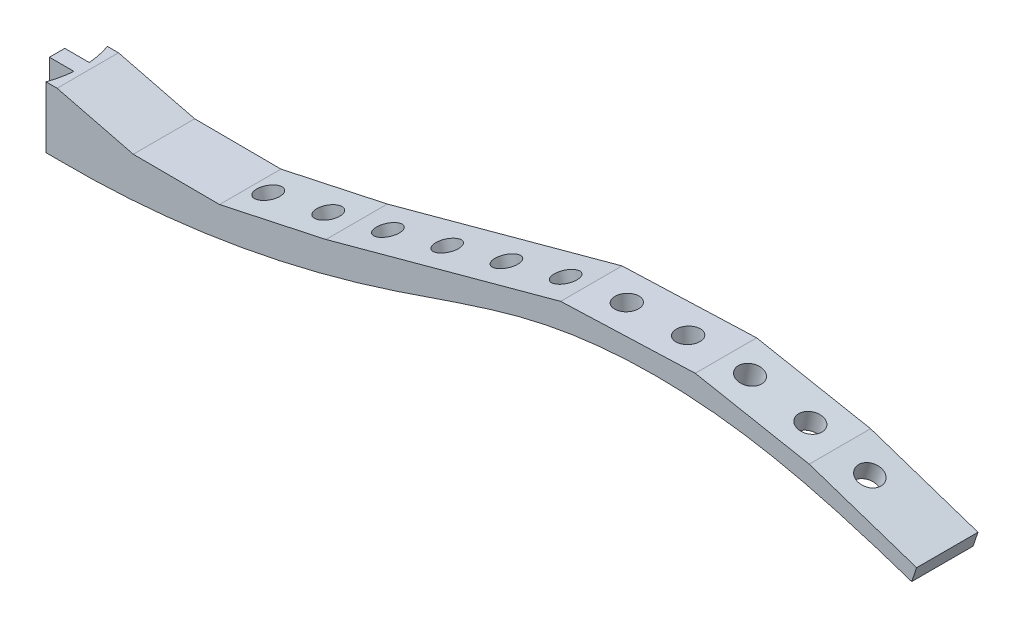
SolidWorks part; units mm, degrees
ref_plane "Front Plane" through (0, 0, 0) normal (0, 0, 1) x (1, 0, 0)
ref_plane "Top Plane" through (0, 0, 0) normal (0, 1, 0) x (1, 0, 0)
ref_plane "Right Plane" through (0, 0, 0) normal (1, 0, 0) x (0, 0, -1)
sketch "Sketch1" plane through (0, 0, 0) normal (0, 0, 1) x (1, 0, 0)
  line L0 (0, 0) -> (0, 12.7)
  line L1 (177.8, 15.7071) -> (176.7812, 12.7)
  line L2 (0, 12.7) -> (15.7663, 8.7557)
  line L3 (15.7663, 8.7557) -> (33.6079, 8.6702)
  line L4 (33.6079, 8.6702) -> (55.6141, 13.4119)
  line L5 (55.6141, 13.4119) -> (104.1724, 26.6053)
  line L6 (104.1724, 26.6053) -> (132.0034, 27.6381)
  line L7 (132.0034, 27.6381) -> (155.5781, 23.1472)
  line L8 (155.5781, 23.1472) -> (177.8, 15.7071)
  spline S1 degree 3 poles (0, 0) (23.0853, -0.2953) (56.9453, 5.5804) (102.5759, 23.5711) (140.7861, 23.9943) (166.1987, 16.2854) (176.7812, 12.7) knots 0 0 0 0 0.381953 0.565829 0.810764 1 1 1 1
  dimension "D1" = 12.7
  dimension "D2" = 3.175
  dimension "D3" = 177.8
  dimension "D4" = 12.7
extrude "Boss-Extrude1" add sketch "Sketch1" along normal mid plane 12.7
sketch "Sketch2" plane through (0, 0, 0) normal (0, 1, 0) x (1, 0, 0)
  line L0 (0, 6.35) -> (-2.2932, 6.35)
  line L1 (0, -6.35) -> (-2.2932, -6.35)
  line L2 (-1.27, 1.5875) -> (-6.35, 1.5875)
  line L3 (-6.35, 1.5875) -> (-6.35, -1.5875)
  line L4 (-6.35, -1.5875) -> (-1.27, -1.5875)
  line L5 (0, 6.35) -> (0, -6.35)
  line L7 (15.7663, 6.35) -> (0, 6.35) construction
  line L8 (15.7663, -6.35) -> (0, -6.35) construction
  line L9 (0, -6.35) -> (0, 6.35) construction
  arc A0 (-2.2932, 6.35) -> (-1.27, 1.5875) centre (-20.2537, 0) cw
  arc A1 (-1.27, -1.5875) -> (-2.2932, -6.35) centre (-20.2537, 0) cw
  point P7 (0, 0)
  point P12 (-6.35, 0)
  point P17 (0, 7.389)
  point P18 (0, 0)
  point P21 (2.6319, 6.35)
  dimension "D1" = 19.05
  dimension "D2" = 1.27
  dimension "D3" = 3.175
  dimension "D4" = 5.08
extrude "Boss-Extrude2" add sketch "Sketch2" along normal up to vertex (12.7 mm away) up to point (0, 12.7, 6.35)
sketch "Sketch4" plane through (-0.2942, 1.3653, 0) normal (-0.2106, 0.9776, 0) x (0.9776, 0.2106, 0)
  line L0 (34.6802, 0) -> (57.1914, 0) construction
  line L1 (34.6802, -6.35) -> (34.6802, 6.35) construction
  line L2 (57.1914, -6.35) -> (57.1914, 6.35) construction
  line L3 (38.4902, 0) -> (51.1902, 0) construction
  circle A0 centre (38.4902, 0) radius 2.4384
  circle A2 centre (51.1902, 0) radius 2.4384
  dimension "D1" = 4.8768
  dimension "D2" = 2
  dimension "D3" = 12.7
  dimension "D4" = 3.81
extrude "Cut-Extrude1" cut sketch "Sketch4" against normal through all
sketch "Sketch5" plane through (0.4298, -1.5817, 0) normal (-0.2622, 0.965, 0) x (0.965, 0.2622, 0)
  line L0 (57.185, 0) -> (107.5037, 0) construction
  line L1 (57.185, -6.35) -> (57.185, 6.35) construction
  line L2 (107.5037, -6.35) -> (107.5037, 6.35) construction
  line L3 (63.8922, 0) -> (76.5922, 0) construction
  circle A0 centre (63.8922, 0) radius 2.4384
  circle A1 centre (76.5922, 0) radius 2.4384
  circle A2 centre (89.2922, 0) radius 2.4384
  circle A3 centre (101.9922, 0) radius 2.4384
  ellipse E1 centre (51.1922, 0) end of major axis (51.1922, -2.4384) minor radius 2.435 construction
  dimension "D1" = 4.8768
  dimension "D2" = 12.7
  dimension "D4" = 12.7
  dimension "D3" = 4
extrude "Cut-Extrude2" cut sketch "Sketch5" against normal through all
sketch "Sketch6" plane through (-0.8427, 22.708, 0) normal (-0.0371, 0.9993, 0) x (0.9993, 0.0371, 0)
  line L0 (105.0874, 0) -> (132.9376, 0) construction
  line L1 (105.0874, -6.35) -> (105.0874, 6.35) construction
  line L2 (132.9376, -6.35) -> (132.9376, 6.35) construction
  line L3 (112.4188, 0) -> (125.1188, 0) construction
  circle A0 centre (112.4188, 0) radius 2.4384
  circle A1 centre (125.1188, 0) radius 2.4384
  ellipse E0 centre (99.7188, 0) end of major axis (99.7188, 2.4384) minor radius 2.3752 construction
  dimension "D1" = 4.8768
  dimension "D2" = 12.7
  dimension "D4" = 12.7
  dimension "D3" = 2
extrude "Cut-Extrude3" cut sketch "Sketch6" against normal through all
sketch "Sketch7" plane through (9.7031, 50.936, 0) normal (0.1871, 0.9823, 0) x (0.9823, -0.1871, 0)
  line L0 (124.4996, 0) -> (148.4982, 0) construction
  line L1 (124.4996, -6.35) -> (124.4996, 6.35) construction
  line L2 (148.4982, -6.35) -> (148.4982, 6.35) construction
  line L3 (129.5784, 0) -> (142.2784, 0) construction
  circle A0 centre (129.5784, 0) radius 2.4384
  circle A1 centre (142.2784, 0) radius 2.4384
  ellipse E0 centre (116.8784, 0) end of major axis (116.8784, 2.4384) minor radius 2.3768 construction
  dimension "D1" = 4.8768
  dimension "D2" = 12.7
  dimension "D4" = 12.7
  dimension "D3" = 2
extrude "Cut-Extrude4" cut sketch "Sketch7" against normal through all
sketch "Sketch8" plane through (22.6509, 67.6528, 0) normal (0.3175, 0.9483, 0) x (0.9483, -0.3175, 0)
  line L0 (140.1798, 0) -> (163.6141, 0) construction
  line L1 (140.1798, -6.35) -> (140.1798, 6.35) construction
  line L2 (163.6141, -6.35) -> (163.6141, 6.35) construction
  circle A0 centre (146.7165, 0) radius 2.4384
  ellipse E0 centre (134.0165, 0) end of major axis (134.0165, 2.4384) minor radius 2.4163 construction
  dimension "D1" = 4.8768
  dimension "D2" = 12.7
extrude "Cut-Extrude5" cut sketch "Sketch8" against normal through all
